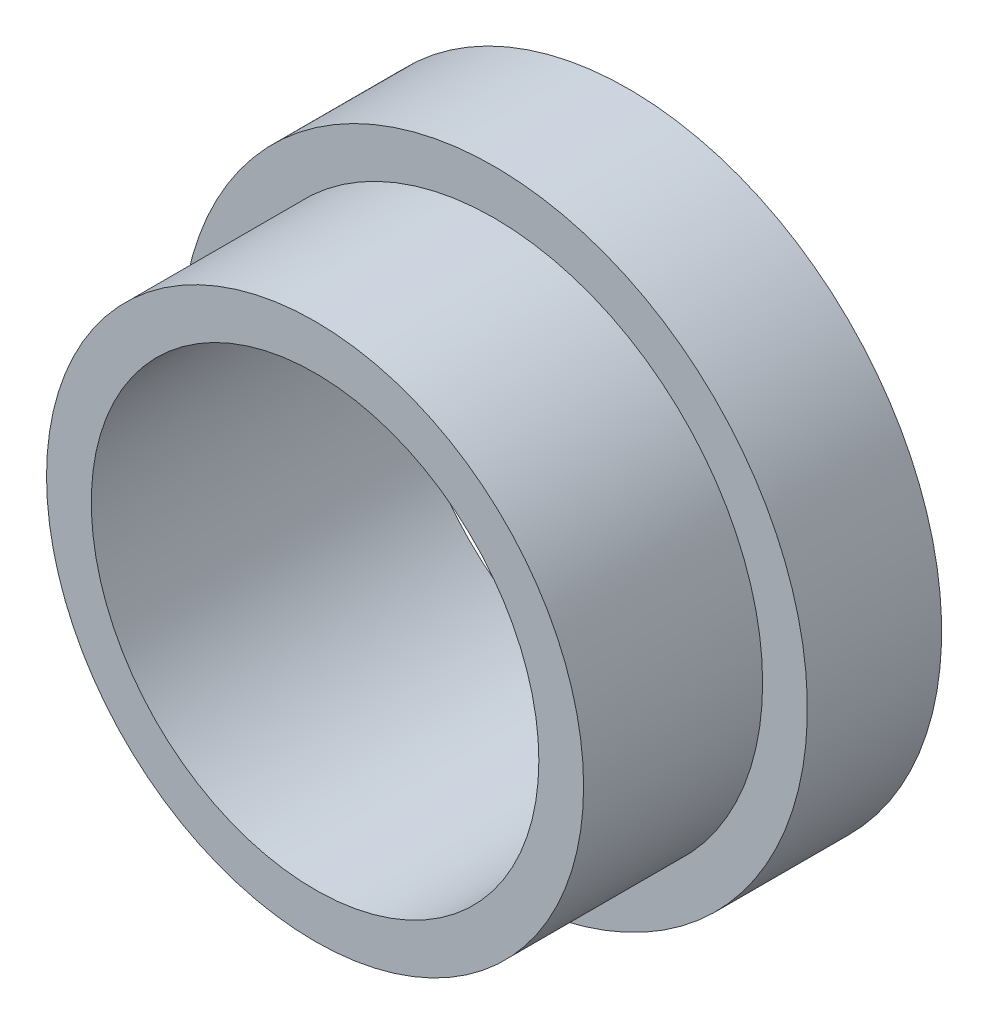
SolidWorks part; units mm, degrees
ref_plane "前视基准面" through (0, 0, 0) normal (0, 0, 1) x (1, 0, 0)
ref_plane "上视基准面" through (0, 0, 0) normal (0, 1, 0) x (1, 0, 0)
ref_plane "右视基准面" through (0, 0, 0) normal (1, 0, 0) x (0, 0, -1)
other "Configuration Table"
sketch "草图1" plane through (0, 0, 0) normal (0, 0, 1) x (1, 0, 0)
  circle A0 centre (0, 0) radius 5
  circle A1 centre (0, 0) radius 6
  dimension "D1" = 10
  dimension "D2" = 12
extrude "凸台-拉伸1" add sketch "草图1" along normal blind 7
sketch "草图2" plane through (0, 0, 0) normal (0, 0, -1) x (-1, 0, 0)
  circle A0 centre (0, 0) radius 7
  circle A1 centre (0, 0) radius 6
  dimension "D1" = 12
  dimension "D2" = 14
extrude "凸台-拉伸2" add sketch "草图2" against normal blind 3
